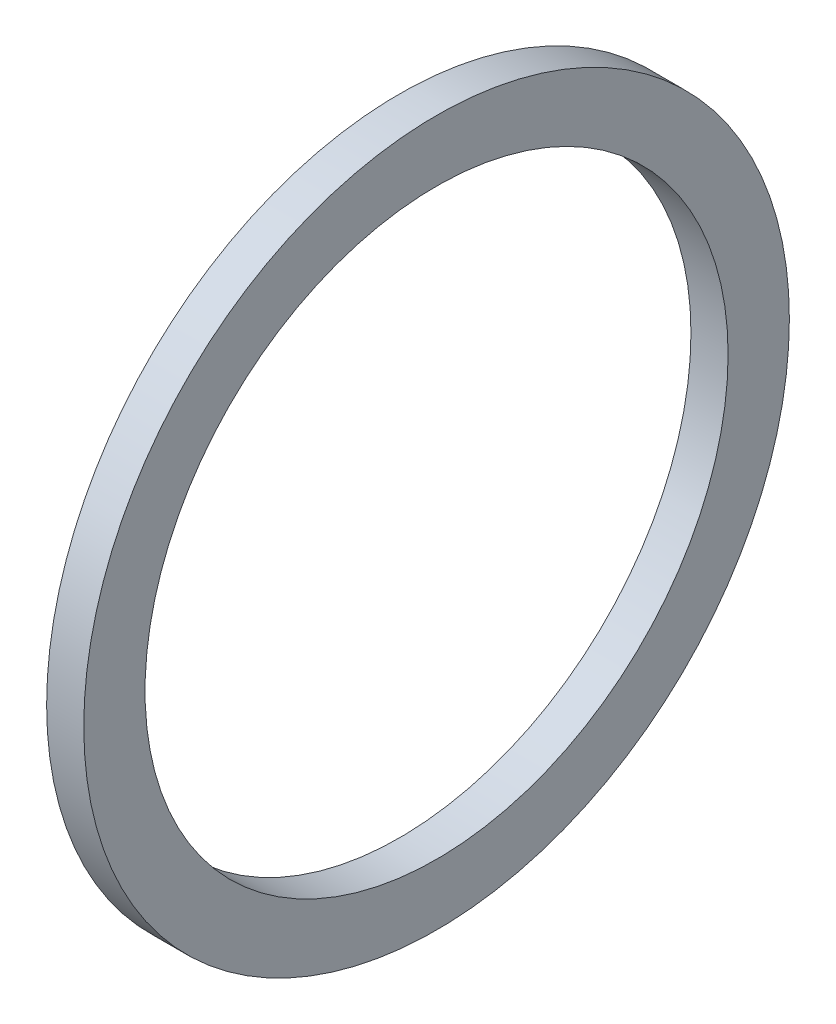
SolidWorks part; units mm, degrees
ref_plane "Front Plane" through (0, 0, 0) normal (0, 0, 1) x (1, 0, 0)
ref_plane "Top Plane" through (0, 0, 0) normal (0, 1, 0) x (1, 0, 0)
ref_plane "Right Plane" through (0, 0, 0) normal (1, 0, 0) x (0, 0, -1)
sketch "Sketch1" plane through (0, 0, 0) normal (1, 0, 0) x (0, 0, -1)
  circle A0 centre (0, 0) radius 7.85
  circle A1 centre (0, 0) radius 9.5
  dimension "D1" = 15.7
  dimension "D2" = 19
extrude "Boss-Extrude1" add sketch "Sketch1" along normal blind 1
